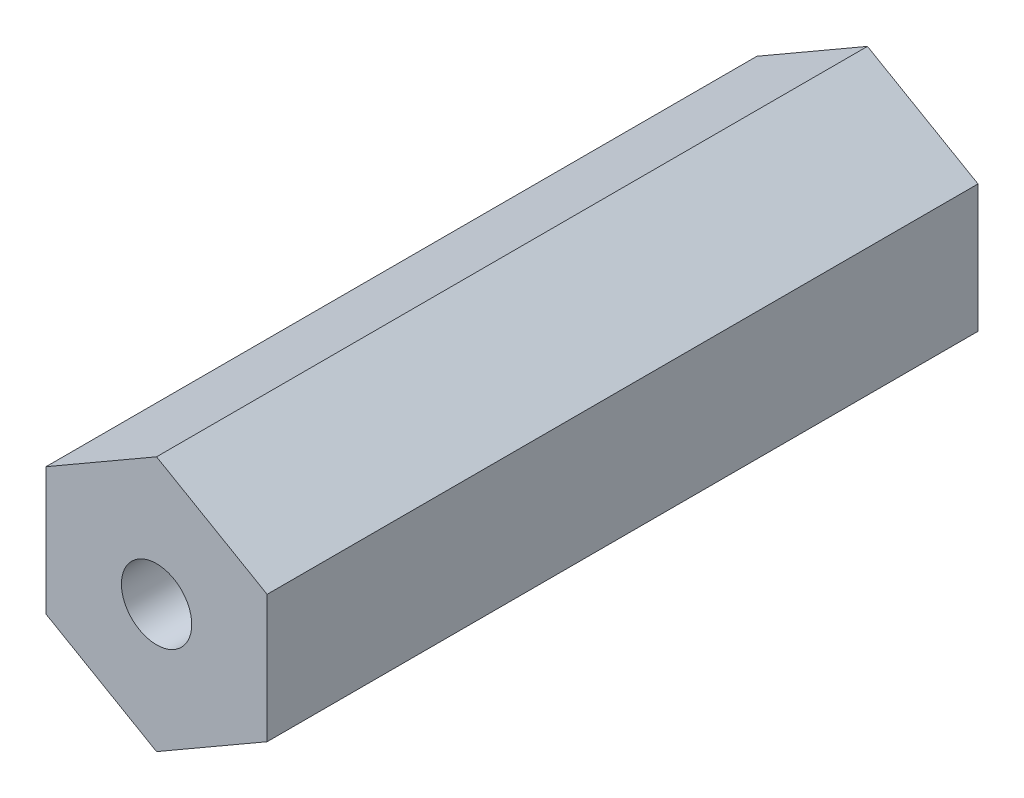
SolidWorks part; units mm, degrees
material "6061 Alloy"
ref_plane "Front Plane" through (0, 0, 0) normal (0, 0, 1) x (1, 0, 0)
ref_plane "Top Plane" through (0, 0, 0) normal (0, 1, 0) x (1, 0, 0)
ref_plane "Right Plane" through (0, 0, 0) normal (1, 0, 0) x (0, 0, -1)
sketch "Sketch1" plane through (0, 0, 0) normal (0, 0, 1) x (1, 0, 0)
  line L1 (0, 7.3323) -> (-6.35, 3.6662)
  line L2 (-6.35, 3.6662) -> (-6.35, -3.6662)
  line L3 (-6.35, -3.6662) -> (0, -7.3323)
  line L4 (0, -7.3323) -> (6.35, -3.6662)
  line L5 (6.35, -3.6662) -> (6.35, 3.6662)
  line L6 (6.35, 3.6662) -> (0, 7.3323)
  circle A0 centre (0, 0) radius 6.35 construction
  circle A1 centre (0, 0) radius 2.0193
  dimension "D1" = 12.7
  dimension "D2" = 4.0386
extrude "Boss-Extrude1" add sketch "Sketch1" along normal blind 40.8305
